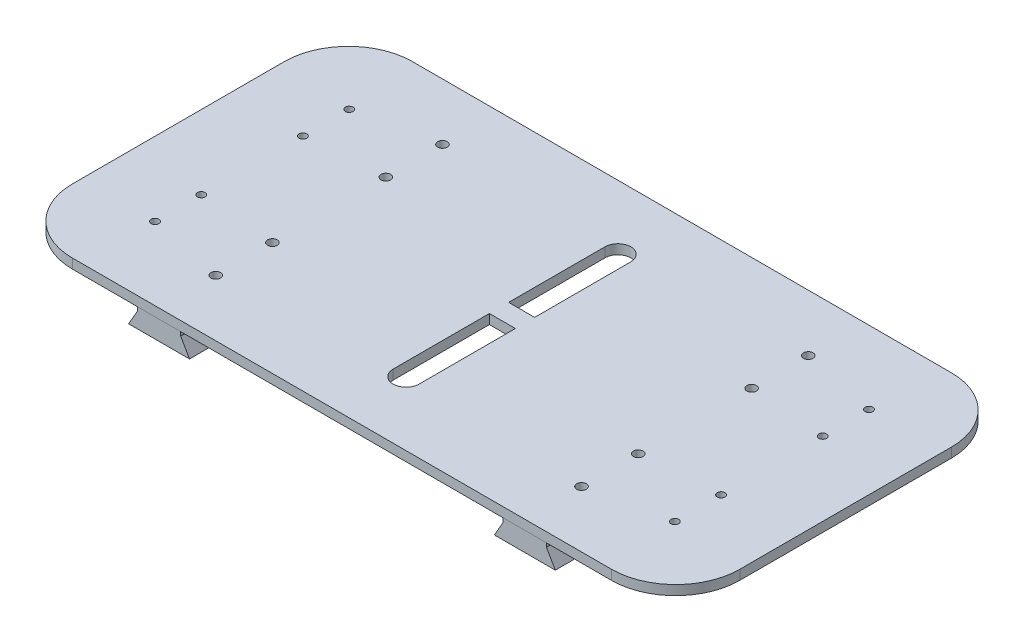
SolidWorks part; units mm, degrees
ref_plane "Front Plane" through (0, 0, 0) normal (0, 0, 1) x (1, 0, 0)
ref_plane "Top Plane" through (0, 0, 0) normal (0, 1, 0) x (1, 0, 0)
ref_plane "Right Plane" through (0, 0, 0) normal (1, 0, 0) x (0, 0, -1)
sketch "Sketch1" plane through (0, 0, 0) normal (0, 0, 1) x (1, 0, 0)
  line L0 (0, 3) -> (208, 3)
  line L1 (0, 0) -> (208, 0)
  line L13 (40.2713, 0) -> (40.2713, -1.2)
  line L14 (40.2713, -1.2) -> (37.5, -6)
  line L15 (37.5, -6) -> (56.5, -6)
  line L16 (56.5, -6) -> (53.7287, -1.2)
  line L17 (53.7287, -1.2) -> (53.7287, 0)
  line L18 (53.7287, 0) -> (40.2713, 0)
  line L19 (104, 3) -> (0, 3) construction
  line L20 (104, 3) -> (104, 0) construction
  line L21 (208, 0) -> (208, 3)
  line L22 (47, 3) -> (47, 0) construction
  line L23 (47, -6) -> (47, 0) construction
  line L24 (154.2713, -1.2) -> (154.2713, 0)
  line L25 (0, 0) -> (0, 3)
  line L26 (0, 3) -> (208, 3) construction
  line L29 (151.5, -6) -> (154.2713, -1.2)
  line L30 (170.5, -6) -> (151.5, -6)
  line L31 (167.7287, -1.2) -> (170.5, -6)
  line L32 (167.7287, 0) -> (167.7287, -1.2)
  line L33 (154.2713, 0) -> (167.7287, 0)
  line L34 (161, -6) -> (161, 3) construction
  dimension "D1" = 3
  dimension "D2" = 208
  dimension "D6" = 60
  dimension "D7" = 60
  dimension "D8" = 19
  dimension "D9" = 1.2
  dimension "D10" = 1.2
  dimension "D11" = 6
  dimension "D20" = 57
  dimension "D21" = 60
  dimension "D22" = 60
  dimension "D23" = 57
extrude "Boss-Extrude1" add sketch "Sketch1" along normal blind 106
fillet "Fillet1" radius 20 4 edges at (0, 1.5, 0) (0, 1.5, 106) (208, 1.5, 0) (208, 1.5, 106)
ref_plane "Plane1" through (0, 0, 0) normal (0, -1, 0) x (-1, 0, 0)
sketch "Sketch3" plane through (0, 3, 0) normal (0, 1, 0) x (1, 0, 0)
  line L0 (104, 0) -> (104, -106) construction
  line L3 (-49.967, -53) -> (208, -53) construction
  line L4 (20, 0) -> (188, 0) construction
  line L5 (20, -106) -> (188, -106) construction
  line L6 (47, -53) -> (47, -106) construction
  line L9 (208, -20) -> (208, -86) construction
  line L10 (0, -20) -> (0, -86) construction
  line L12 (20, -106) -> (188, -106) construction
  line L13 (104, -20) -> (104, -86) construction
  line L14 (108.05, -20) -> (108.05, -86)
  line L15 (99.95, -20) -> (99.95, -86)
  line L16 (108.05, -50) -> (108.05, -56) construction
  line L17 (99.95, -50) -> (108.05, -50)
  line L18 (99.95, -50) -> (99.95, -56)
  line L19 (99.95, -56) -> (108.05, -56)
  line L20 (108.05, -50) -> (108.05, -56)
  circle A1 centre (47, -70.6667) radius 1.5
  circle A2 centre (47, -88.3333) radius 1.5
  circle A20 centre (161, -88.3333) radius 1.5
  circle A21 centre (161, -70.6667) radius 1.5
  circle A22 centre (161, -17.6667) radius 1.5
  circle A23 centre (161, -35.3333) radius 1.5
  circle A24 centre (47, -17.6667) radius 1.5
  circle A25 centre (47, -35.3333) radius 1.5
  arc A26 (108.05, -20) -> (99.95, -20) centre (104, -20) ccw
  arc A27 (99.95, -86) -> (108.05, -86) centre (104, -86) ccw
  point P7 (104, -53)
  point P38 (104, -15.95)
  point P39 (104, -90.05)
  dimension "D2" = 3
  dimension "D3" = 17.6667
  dimension "D4" = 3
  dimension "D6" = 8.1
  dimension "D7" = 74.1
  dimension "D1" = 27
  dimension "D5" = 17.6667
  dimension "D8" = 257.967
  dimension "D9" = 6
  dimension "D10" = 3
extrude "Cut-Extrude3" cut sketch "Sketch3" along direction (0, 1, 0) on the side against the normal blind 10 contours L14 A26 L15 L17 | L15 A27 L14 L19
sketch "Sketch6" plane through (0, 3, 0) normal (0, 1, 0) x (1, 0, 0)
  line L1 (104, -106) -> (104, 0) construction
  line L3 (0, -53) -> (208, -53) construction
  line L6 (208, -86) -> (208, -20) construction
  line L7 (0, -86) -> (0, -20) construction
  line L8 (20, 0) -> (188, 0) construction
  line L9 (20, -106) -> (188, -106) construction
  circle A0 centre (185, -22.74) radius 1.2
  circle A1 centre (185, -37.16) radius 1.2
  circle A2 centre (23, -22.74) radius 1.2
  circle A3 centre (23, -37.16) radius 1.2
  circle A4 centre (23, -83.26) radius 1.2
  circle A5 centre (23, -68.84) radius 1.2
  circle A6 centre (185, -83.26) radius 1.2
  circle A7 centre (185, -68.84) radius 1.2
  point P7 (0, 0)
  point P8 (196.2263, -53.2124)
  point P9 (208, -53)
  point P14 (0, -53)
  point P29 (104, 0)
  point P32 (104, -106)
  point P38 (184.3451, -7.9637)
  dimension "D3" = 2.4
  dimension "D4" = 2.4
  dimension "D5" = 3
  dimension "D1" = 14.42
  dimension "D2" = 3
  dimension "D6" = 22.74
extrude "Cut-Extrude4" cut sketch "Sketch6" against normal blind 10
split "Split1" trim tools "Plane1" bodies to split 109 resulting bodies 105 106 107
